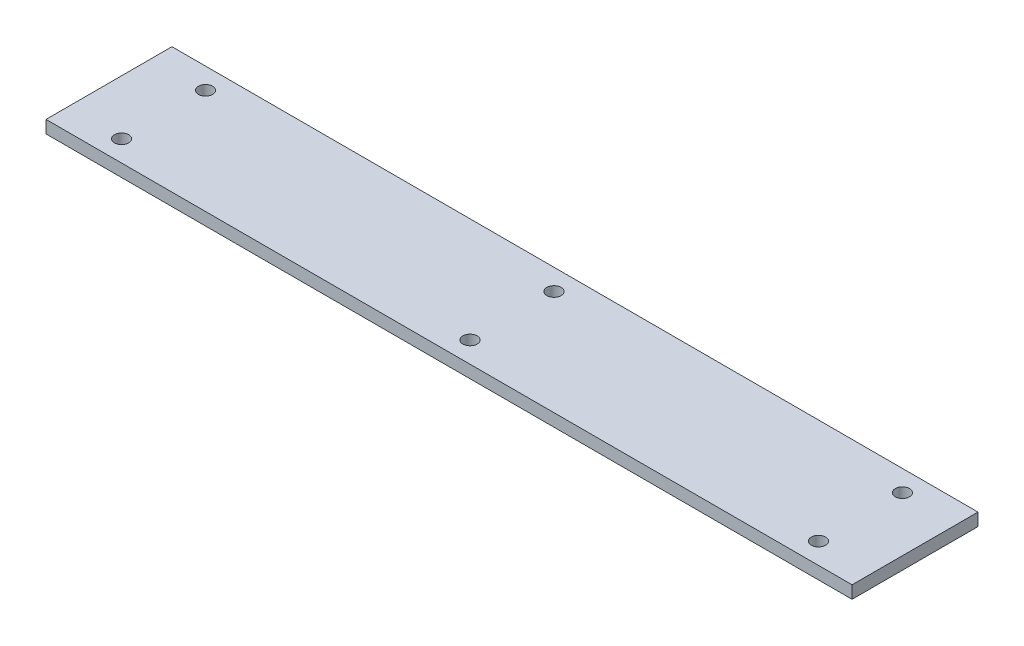
SolidWorks part; units mm, degrees
ref_plane "Front Plane" through (0, 0, 0) normal (0, 0, 1) x (1, 0, 0)
ref_plane "Top Plane" through (0, 0, 0) normal (0, 1, 0) x (1, 0, 0)
ref_plane "Right Plane" through (0, 0, 0) normal (1, 0, 0) x (0, 0, -1)
sketch "Sketch1" plane through (0, 0, 0) normal (0, 1, 0) x (1, 0, 0)
  line L1 (0, 0) -> (192, 0)
  line L2 (0, 0) -> (0, 30)
  line L3 (0, 30) -> (192, 30)
  line L4 (192, 0) -> (192, 30)
  circle A0 centre (13, 25) radius 1.7
  circle A1 centre (13, 5) radius 1.7
  circle A2 centre (96, 25) radius 1.7
  circle A3 centre (96, 5) radius 1.7
  circle A4 centre (179, 25) radius 1.7
  circle A5 centre (179, 5) radius 1.7
  dimension "D3" = 3.4
  dimension "D4" = 3.4
  dimension "D5" = 3.4
  dimension "D6" = 3.4
  dimension "D7" = 3.4
  dimension "D8" = 3.4
  dimension "D9" = 13
  dimension "D10" = 13
  dimension "D11" = 20
  dimension "D12" = 5
  dimension "D13" = 83
  dimension "D14" = 20
  dimension "D15" = 5
  dimension "D16" = 83
  dimension "D17" = 20
  dimension "D18" = 5
  dimension "D19" = 13
  dimension "D20" = 13
  dimension "D1" = 192
  dimension "D2" = 30
extrude "Boss-Extrude1" add sketch "Sketch1" along normal blind 3
